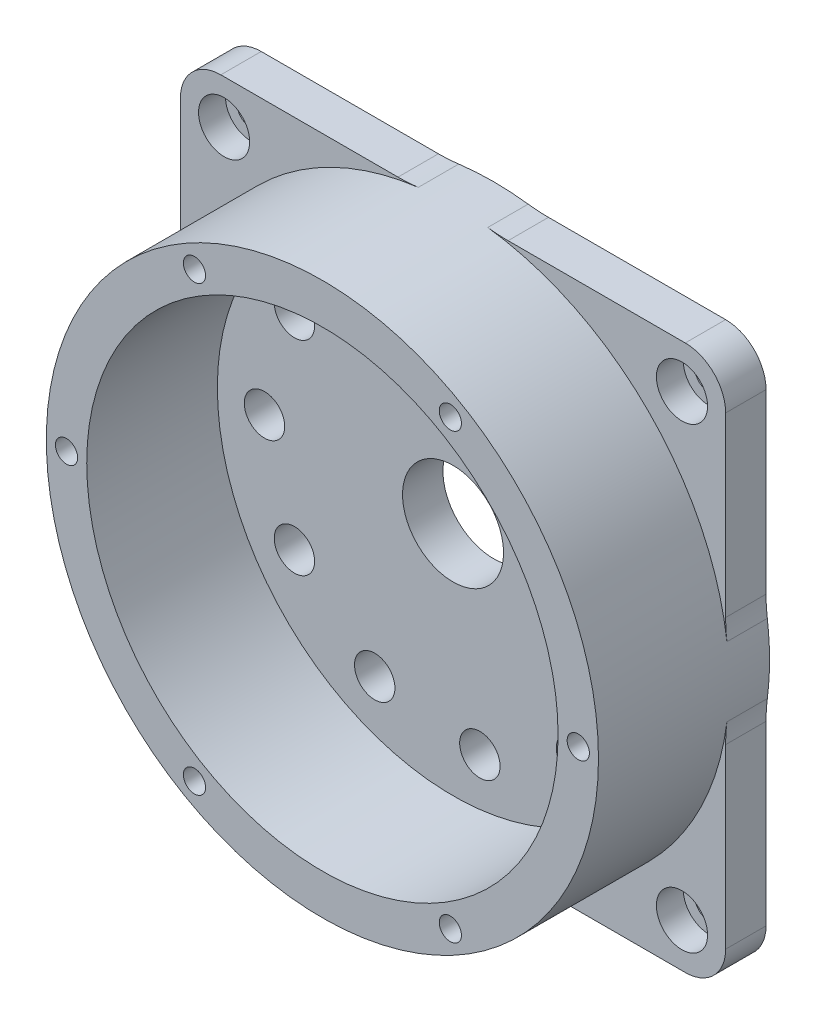
SolidWorks part; units mm, degrees
material "6061-T6 (SS)"
ref_plane "Front Plane" through (0, 0, 0) normal (1, 0, 0) x (0, 1, 0)
ref_plane "Top Plane" through (0, 0, 0) normal (0, 0, 1) x (0, 1, 0)
ref_plane "Right Plane" through (0, 0, 0) normal (0, 1, 0) x (-1, 0, 0)
sketch "Sketch1" plane through (0, 0, 0) normal (0, 0, 1) x (0, 1, 0)
  circle A0 centre (0, 0) radius 41
  circle A1 centre (0, 28) radius 3
  circle A2 centre (15.1379, 23.5551) radius 3
  circle A3 centre (25.4697, 11.6316) radius 3
  circle A4 centre (27.715, -3.9848) radius 3
  circle A5 centre (21.161, -18.3361) radius 3
  circle A6 centre (7.8885, -26.8658) radius 3
  circle A7 centre (-7.8885, -26.8658) radius 3
  circle A8 centre (-21.161, -18.3361) radius 3
  circle A9 centre (-27.715, -3.9848) radius 3
  circle A10 centre (-25.4697, 11.6316) radius 3
  circle A11 centre (-15.1379, 23.5551) radius 3
  point P28 (0, 0)
  dimension "D1" = 82
  dimension "D2" = 6
  dimension "D3" = 28
  dimension "D4" = 11
extrude "Boss-Extrude1" add sketch "Sketch1" against normal blind 6 contours A0 | A1 | A2 | A3 | A4 | A5 | A6 | A7 | A8 | A9 | A10 | A11
sketch "Sketch3" plane through (0, 0, 0) normal (0, 0, 1) x (1, 0, 0)
  circle A0 centre (0, 0) radius 41 construction
  circle A1 centre (0, 0) radius 41
  circle A2 centre (0, 0) radius 35
  dimension "D1" = 70
extrude "Boss-Extrude2" add sketch "Sketch3" along normal blind 19.4
sketch "Sketch5" plane through (0, 0, 0) normal (0, 0, 1) x (1, 0, 0)
  circle A0 centre (0, 0) radius 7.5
  dimension "D1" = 15
extrude "Cut-Extrude1" cut sketch "Sketch5" against normal through all contours A0
sketch "Sketch6" plane through (0, 0, 19.4) normal (0, 0, 1) x (1, 0, 0)
  line L0 (-41, 0) -> (-35, 0) construction
  circle A0 centre (-38, 0) radius 1.65
  circle A3 centre (-19, 32.909) radius 1.65
  circle A4 centre (19, 32.909) radius 1.65
  circle A5 centre (38, 0) radius 1.65
  circle A6 centre (19, -32.909) radius 1.65
  circle A7 centre (-19, -32.909) radius 1.65
  circle A13 centre (0, 0) radius 41 construction
  circle A14 centre (0, 0) radius 35 construction
  point P5 (-38, 0)
  point P23 (0, 0)
  dimension "D1" = 3.3
  dimension "D2" = 6
extrude "Cut-Extrude2" cut sketch "Sketch6" against normal blind 10
sketch "Sketch7" plane through (0, 0, -6) normal (0, 0, -1) x (1, 0, 0)
  line L0 (6.484, 40.484) -> (40.484, 40.484)
  line L1 (40.484, 40.484) -> (40.484, 6.484)
  line L2 (40.484, 40.484) -> (0, 0) construction
  line L3 (0, 0) -> (7.5, 0) construction
  circle A1 centre (34, 34) radius 2.1
  circle A2 centre (0, 0) radius 7.5 construction
  circle A3 centre (0, 0) radius 41 construction
  circle A4 centre (0, 0) radius 41
  arc A5 (6.484, 40.484) -> (40.484, 6.484) centre (0, 0) ccw
  circle M18 centre (0, 0) radius 41
  dimension "D1" = 4.2
  dimension "D2" = 34
  dimension "D3" = 34
  dimension "D4" = 34
  dimension "D5" = 34
  dimension "D6" = 45
extrude "Boss-Extrude3" add sketch "Sketch7" against normal blind 6 contours L1 L0 A1 M18
fillet "Fillet1" radius 6 1 edges at (40.484, -40.484, -3)
fillet "Fillet2" radius 24 2 edges at (6.484, -40.484, -3) (40.484, -6.484, -3)
sketch "Sketch9" plane through (0, 0, 0) normal (0, 0, 1) x (1, 0, 0)
  line L2 (8.1737, -40.484) -> (34.484, -40.484)
  line L3 (40.484, -34.484) -> (40.484, -8.1737)
  line L4 (8.1737, -40.484) -> (34.484, -40.484)
  line L5 (40.484, -34.484) -> (40.484, -8.1737)
  circle A0 centre (34, -34) radius 2.1 construction
  circle A1 centre (34, -34) radius 2.1
  arc A4 (5.1557, -40.6745) -> (40.6745, -5.1557) centre (0, 0) ccw
  arc A5 (8.1737, -40.484) -> (5.1557, -40.6745) centre (8.1737, -64.484) ccw
  arc A6 (34.484, -40.484) -> (40.484, -34.484) centre (34.484, -34.484) ccw
  arc A7 (40.6745, -5.1557) -> (40.484, -8.1737) centre (64.484, -8.1737) ccw
  arc A8 (5.1557, -40.6745) -> (40.6745, -5.1557) centre (0, 0) ccw
  arc A9 (8.1737, -40.484) -> (5.1557, -40.6745) centre (8.1737, -64.484) ccw
  arc A10 (34.484, -40.484) -> (40.484, -34.484) centre (34.484, -34.484) ccw
  arc A11 (40.6745, -5.1557) -> (40.484, -8.1737) centre (64.484, -8.1737) ccw
  point P0 (34, -34)
  dimension "D1" = 0
hole_wizard "CBORE for M4 Hex Head Cap Screw1" positions "Sketch9" profile "Sketch10" counterbore size "M4" standard "ISO" end condition through all
sketch "Sketch10" plane through (34, -34, 0) normal (1, 0, 0) x (0, -1, 0)
  line L0 (0, 0) -> (0, 6)
  line L1 (0, 6) -> (2.1, 6)
  line L3 (2.1, 6) -> (2.1, 4)
  line L4 (2.1, 4) -> (3.8, 4)
  line L5 (3.8, 4) -> (3.8, 0)
  line L7 (3.8, 0) -> (0, 0)
  line L11 (0, -6.35) -> (0, 107.95) construction
  dimension "Thru Hole Dia." = 4.2
  dimension "Thru Hole Depth" = 6
  dimension "C'Bore Dia." = 7.6
  dimension "C'Bore Depth" = 4
pattern_circular "CirPattern1" count 4 over 360 about axis through (0, 0, 0) along (0, 0, 1) of "CBORE for M4 Hex Head Cap Screw1", "Fillet2", "Fillet1", "Boss-Extrude3"
